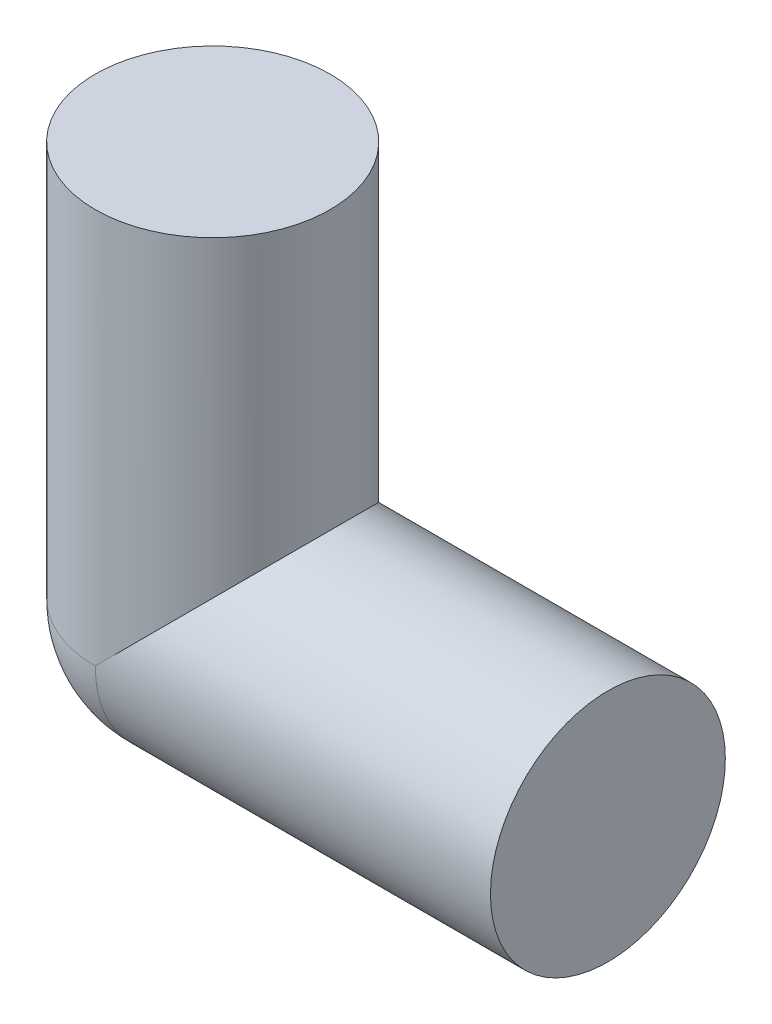
SolidWorks part; units mm, degrees
material "Brass"
ref_plane "Front Plane" through (0, 0, 0) normal (0, 0, 1) x (1, 0, 0)
ref_plane "Top Plane" through (0, 0, 0) normal (0, 1, 0) x (1, 0, 0)
ref_plane "Right Plane" through (0, 0, 0) normal (1, 0, 0) x (0, 0, -1)
sketch "Sketch1" plane through (0, 0, 0) normal (0, 1, 0) x (1, 0, 0)
  circle A0 centre (0, 0) radius 8
  dimension "D1" = 16
extrude "Boss-Extrude1" add sketch "Sketch1" along normal blind 26.924
sketch "Sketch2" plane through (0, 0, 0) normal (1, 0, 0) x (0, 0, -1)
  circle A0 centre (0, 0) radius 8
extrude "Boss-Extrude2" add sketch "Sketch2" along normal blind 26.924
sketch "Sketch3" plane through (0, 0, 0) normal (-1, 0, 0) x (0, 0, 1)
  line L0 (-8, 0) -> (8, 0)
  line L1 (0, 0) -> (12.5512, 0) construction
  arc A0 (-8, 0) -> (8, 0) centre (0, 0) ccw
revolve "Revolve1" add sketch "Sketch3" angle 90 about L1
